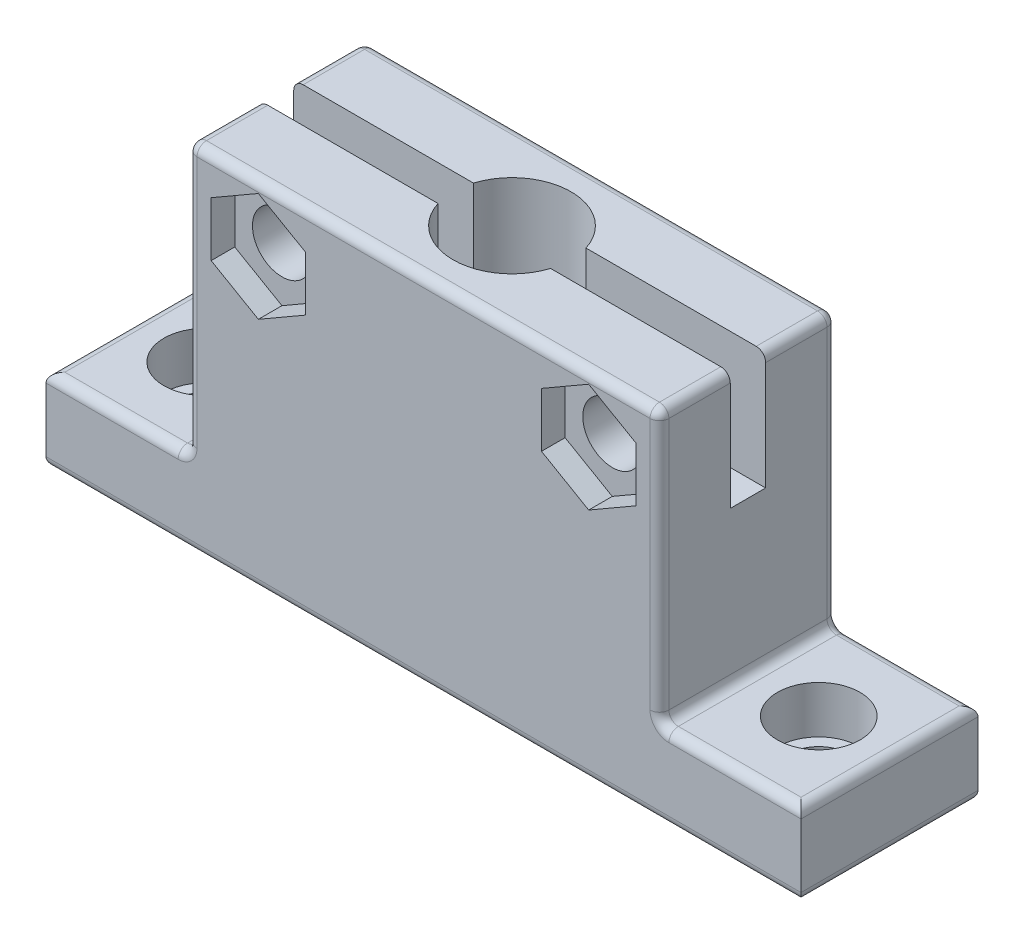
SolidWorks part; units mm, degrees
material "1.4511 (X3CrNb17)"
ref_plane "前视基准面" through (0, 0, 0) normal (0, 0, 1) x (1, 0, 0)
ref_plane "上视基准面" through (0, 0, 0) normal (0, 1, 0) x (1, 0, 0)
ref_plane "右视基准面" through (0, 0, 0) normal (1, 0, 0) x (0, 0, -1)
sketch "草图1" plane through (0, 0, 0) normal (0, 1, 0) x (1, 0, 0)
  line L1 (-32, 7.5) -> (32, 7.5)
  line L2 (-32, 7.5) -> (-32, -7.5)
  line L3 (-32, -7.5) -> (32, -7.5)
  line L4 (32, 7.5) -> (32, -7.5)
  line L5 (-32, 7.5) -> (32, -7.5) construction
  line L6 (-32, -7.5) -> (32, 7.5) construction
  point P0 (0, 0)
  dimension "D1" = 64
  dimension "D2" = 15
extrude "凸台-拉伸1" add sketch "草图1" along normal blind 7
sketch "草图2" plane through (0, 7, 0) normal (0, 1, 0) x (1, 0, 0)
  line L1 (-20, 7.5) -> (20, 7.5)
  line L2 (-20, 7.5) -> (-20, -7.5)
  line L3 (-20, -7.5) -> (20, -7.5)
  line L4 (20, 7.5) -> (20, -7.5)
  line L5 (-20, 7.5) -> (20, -7.5) construction
  line L6 (-20, -7.5) -> (20, 7.5) construction
  point P0 (0, 0)
  dimension "D1" = 40
  dimension "D2" = 15
extrude "凸台-拉伸2" add sketch "草图2" along normal blind 23
sketch "草图3" plane through (0, 30, 0) normal (0, 1, 0) x (1, 0, 0)
  circle A0 centre (0, 0) radius 5
  dimension "D1" = 10
extrude "切除-拉伸1" cut sketch "草图3" against normal blind 20
sketch "草图4" plane through (0, 30, 0) normal (0, 1, 0) x (1, 0, 0)
  line L0 (20, -7.5) -> (20, 7.5) construction
  line L1 (-20, 1.5) -> (20, 1.5)
  line L2 (-20, 1.5) -> (-20, -1.5)
  line L3 (-20, -1.5) -> (20, -1.5)
  line L4 (20, 1.5) -> (20, -1.5)
  line L5 (-20, 1.5) -> (20, -1.5) construction
  line L6 (-20, -1.5) -> (20, 1.5) construction
  point P0 (0, 0)
  dimension "D1" = 3
extrude "切除-拉伸2" cut sketch "草图4" against normal blind 10
sketch "草图5" plane through (0, 0, 7.5) normal (0, 0, 1) x (1, 0, 0)
  line L0 (-14, 24.5) -> (14, 24.5) construction
  line L1 (-20, 30) -> (-20, 7) construction
  line L2 (-20, 30) -> (20, 30) construction
  dimension "D1" = 28
  dimension "D2" = 6
  dimension "D3" = 5.5
hole_wizard "M5 螺纹孔的螺纹孔钻头1" positions "草图6" profile "草图7" hole size "M5" standard "GB" end condition through all
sketch "草图6" plane through (0, 0, 7.5) normal (0, 0, 1) x (1, 0, 0)
  point P0 (-14, 24.5)
  point P3 (14, 24.5)
sketch "草图7" plane through (-14, 24.5, 7.5) normal (1, 0, 0) x (0, -1, 0)
  line L0 (0, 0) -> (0, 15)
  line L1 (0, 15) -> (2.5, 15)
  line L2 (2.5, 15) -> (2.5, 0)
  line L5 (2.5, 0) -> (0, 0)
  line L11 (0, -6.35) -> (0, 107.95) construction
  dimension "通孔孔直径" = 5
  dimension "通孔孔深度" = 15
sketch "草图8" plane through (0, 7, 0) normal (0, 1, 0) x (1, 0, 0)
  line L1 (-32, 7.5) -> (-32, -7.5) construction
  line L2 (-32, -7.5) -> (-20, -7.5) construction
  circle A0 centre (-26, 0) radius 3.5
  dimension "D1" = 7
  dimension "D2" = 6
  dimension "D3" = 7.5
extrude "切除-拉伸3" cut sketch "草图8" against normal blind 4
hole_wizard "M5 螺纹孔的螺纹孔钻头2" positions "草图9" profile "草图10" hole size "M5" standard "GB" end condition through all
sketch "草图9" plane through (0, 3, 0) normal (0, 1, 0) x (1, 0, 0)
  point P0 (-26, 0)
sketch "草图10" plane through (-26, 3, 0) normal (1, 0, 0) x (0, 0, 1)
  line L0 (0, 0) -> (0, 3)
  line L1 (0, 3) -> (2.5, 3)
  line L2 (2.5, 3) -> (2.5, 0)
  line L5 (2.5, 0) -> (0, 0)
  line L11 (0, -6.35) -> (0, 107.95) construction
  dimension "通孔孔直径" = 5
  dimension "通孔孔深度" = 3
mirror "镜向1" about plane through (0, 0, 0) normal (1, 0, 0) of "M5 螺纹孔的螺纹孔钻头2", "切除-拉伸3"
sketch "草图12" plane through (0, 0, 7.5) normal (0, 0, 1) x (1, 0, 0)
  line L1 (-14, 19.8812) -> (-10, 22.1906)
  line L2 (-10, 22.1906) -> (-10, 26.8094)
  line L3 (-10, 26.8094) -> (-14, 29.1188)
  line L4 (-14, 29.1188) -> (-18, 26.8094)
  line L5 (-18, 26.8094) -> (-18, 22.1906)
  line L6 (-18, 22.1906) -> (-14, 19.8812)
  line L7 (14, 19.8812) -> (18, 22.1906)
  line L8 (18, 22.1906) -> (18, 26.8094)
  line L9 (18, 26.8094) -> (14, 29.1188)
  line L10 (14, 29.1188) -> (10, 26.8094)
  line L11 (10, 26.8094) -> (10, 22.1906)
  line L12 (10, 22.1906) -> (14, 19.8812)
  circle A0 centre (-14, 24.5) radius 4 construction
  circle A1 centre (14, 24.5) radius 4 construction
  dimension "D1" = 8
  dimension "D2" = 8
  dimension "D3" = 4
  dimension "D4" = 4
extrude "切除-拉伸5" cut sketch "草图12" against normal blind 2
fillet "圆角1" radius 0.8 22 edges at (-20, 18.5, 7.5) (-20, 18.5, -7.5) (20, 18.5, 7.5) (20, 18.5, -7.5) (-26, 7, 7.5) (-26, 7, -7.5) (26, 7, 7.5) (26, 7, -7.5) (0, 0, -7.5) (0, 0, 7.5) (0, 30, -7.5) (0, 30, 7.5) (20, 30, -4.5) (20, 30, 4.5) (-20, 30, -4.5) (-20, 30, 4.5) (-20, 7, 0) (20, 7, 0) (32, 0, 0) (32, 7, 0) (-32, 7, 0) (-32, 0, 0)
